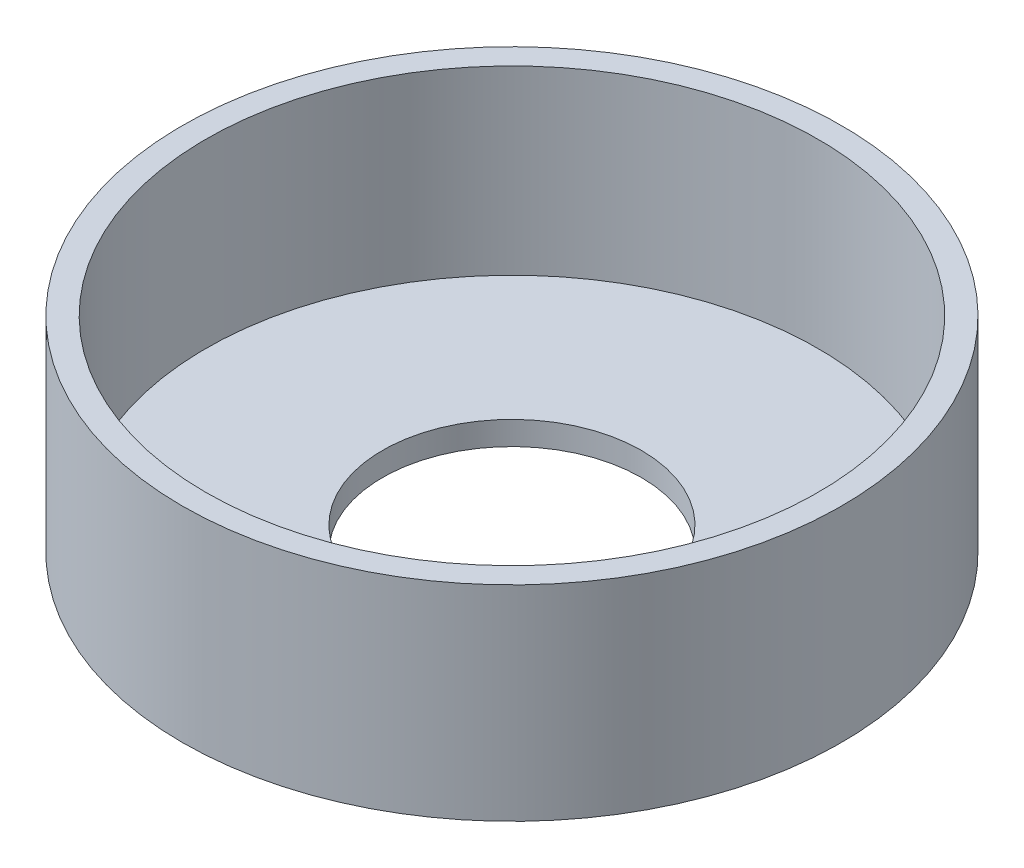
SolidWorks part; units mm, degrees
ref_plane "Front Plane" through (0, 0, 0) normal (0, 0, 1) x (1, 0, 0)
ref_plane "Top Plane" through (0, 0, 0) normal (0, 1, 0) x (1, 0, 0)
ref_plane "Right Plane" through (0, 0, 0) normal (1, 0, 0) x (0, 0, -1)
sketch "Sketch1" plane through (0, 0, 0) normal (0, 1, 0) x (1, 0, 0)
  circle A0 centre (0, 0) radius 17.78
  dimension "D1" = 35.56
extrude "Boss-Extrude1" add sketch "Sketch1" along normal blind 11.049
shell "Shell1" thickness 1.27
sketch "Sketch2" plane through (0, 1.27, 0) normal (0, 1, 0) x (1, 0, 0)
  circle A0 centre (0, 0) radius 6.985
  dimension "D1" = 13.97
extrude "Cut-Extrude1" cut sketch "Sketch2" against normal through all
